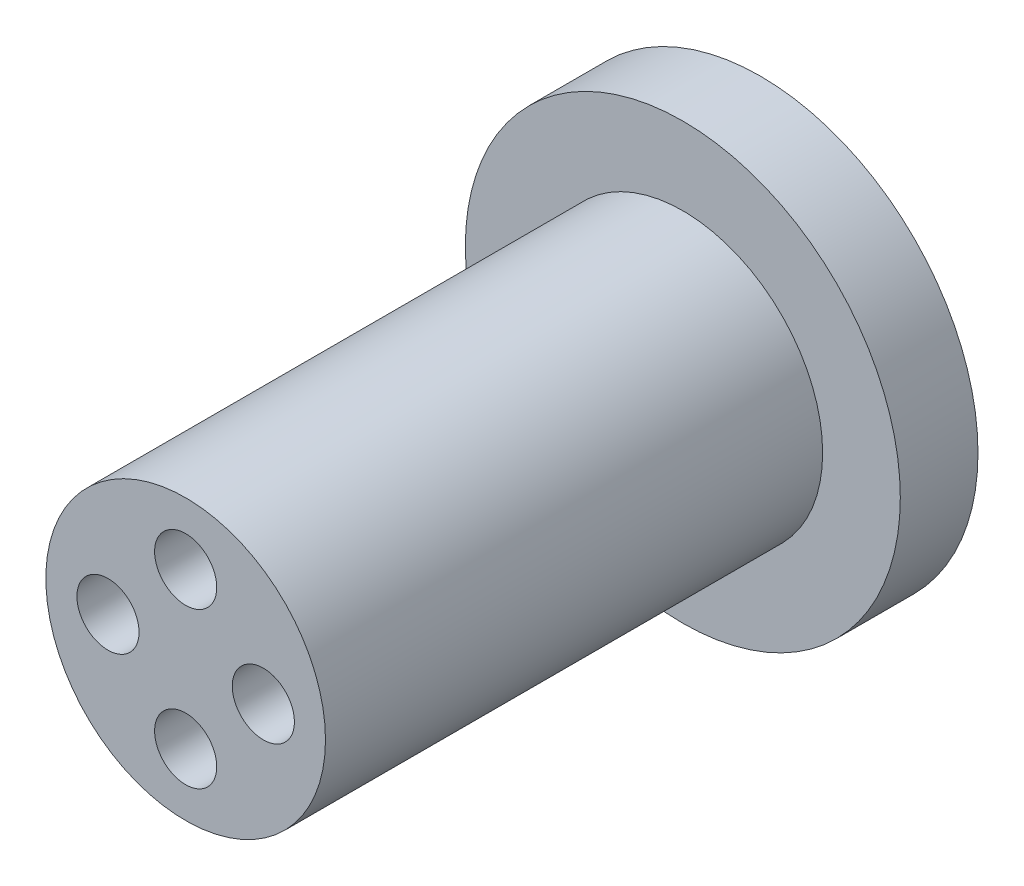
SolidWorks part; units mm, degrees
ref_plane "前视基准面" through (0, 0, 0) normal (0, 0, 1) x (1, 0, 0)
ref_plane "上视基准面" through (0, 0, 0) normal (0, 1, 0) x (1, 0, 0)
ref_plane "右视基准面" through (0, 0, 0) normal (1, 0, 0) x (0, 0, -1)
other "Configuration Table"
sketch "Sketch1" plane through (0, 0, 0) normal (0, 0, 1) x (1, 0, 0)
  circle A0 centre (0, 0) radius 7
  dimension "D1" = 14
extrude "Boss-Extrude1" add sketch "Sketch1" along normal blind 2.5
sketch "Sketch2" plane through (0, 0, 2.5) normal (0, 0, 1) x (1, 0, 0)
  circle A0 centre (0, 0) radius 4.5
  dimension "D1" = 9
extrude "Boss-Extrude2" add sketch "Sketch2" along normal blind 16
sketch "Sketch3" plane through (0, 0, 18.5) normal (0, 0, 1) x (1, 0, 0)
  circle A0 centre (0, 0) radius 2.5 construction
  circle A1 centre (0, 2.5) radius 1
  circle A2 centre (2.5, 0) radius 1
  circle A3 centre (0, -2.5) radius 1
  circle A4 centre (-2.5, 0) radius 1
  point P14 (0, 0)
  dimension "D1" = 5
  dimension "D2" = 2
extrude "Cut-Extrude1" cut sketch "Sketch3" against normal blind 5
